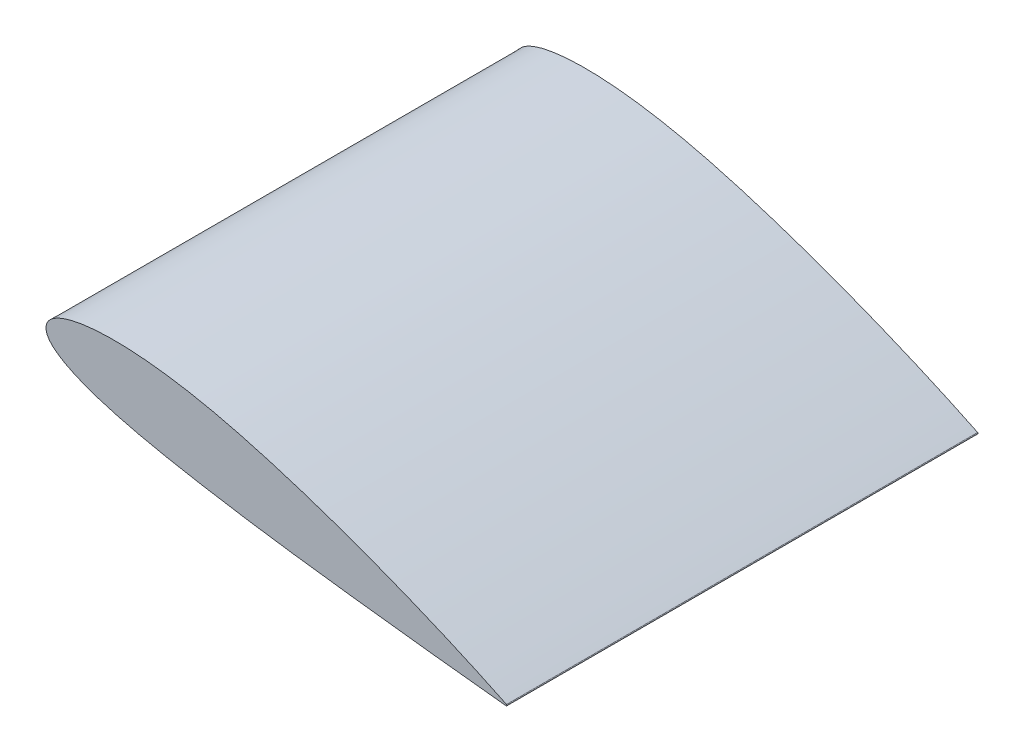
SolidWorks part; units mm, degrees
ref_plane "Front Plane"
ref_plane "Top Plane" through (0, 0, 0) normal (0, 1, 0) x (1, 0, 0)
ref_plane "Right Plane" through (0, 0, 0) normal (1, 0, 0) x (0, 0, -1)
curve "Curve1"
  spline degree 3 poles (25.4, 0.0399, 0) (25.378, 0.0455, 0) (25.2876, 0.0686, 0) (25.0833, 0.1169, 0) (24.7444, 0.1986, 0) (24.2743, 0.3079, 0) (23.6782, 0.4427, 0) (22.9624, 0.5992, 0) (22.1339, 0.7718, 0) (21.2017, 0.9572, 0) (20.1756, 1.1494, 0) (19.0665, 1.3442, 0) (17.8862, 1.536, 0) (16.6475, 1.7203, 0) (15.3641, 1.8922, 0) (14.0499, 2.0465, 0) (12.7195, 2.1793, 0) (11.3871, 2.2848, 0) (10.064, 2.3615, 0) (8.7644, 2.3973, 0) (7.5041, 2.3875, 0) (6.3019, 2.3314, 0) (5.1723, 2.2307, 0) (4.1285, 2.0871, 0) (3.1827, 1.9058, 0) (2.3457, 1.6908, 0) (1.6261, 1.4497, 0) (1.0314, 1.1874, 0) (0.5652, 0.911, 0) (0.2297, 0.6234, 0) (0.0247, 0.3197, 0) (-0.026, -0.0026, 0) (0.0875, -0.3078, 0) (0.3448, -0.5657, 0) (0.7235, -0.7848, 0) (1.2228, -0.973, 0) (1.8395, -1.1305, 0) (2.5685, -1.2568, 0) (3.4023, -1.3511, 0) (4.3324, -1.4141, 0) (5.3492, -1.447, 0) (6.4428, -1.4525, 0) (7.6021, -1.4335, 0) (8.8157, -1.3943, 0) (10.0756, -1.3404, 0) (11.3691, -1.2731, 0) (12.6822, -1.1887, 0) (13.997, -1.0934, 0) (15.2991, -0.9906, 0) (16.5743, -0.8837, 0) (17.8086, -0.7765, 0) (18.9885, -0.6699, 0) (20.1008, -0.5673, 0) (21.1332, -0.4696, 0) (22.074, -0.3787, 0) (22.9125, -0.2964, 0) (23.6391, -0.2232, 0) (24.2454, -0.161, 0) (24.7246, -0.1111, 0) (25.0709, -0.0749, 0) (25.2812, -0.0522, 0) (25.3756, -0.0424, 0) (25.4, -0.0399, 0) knots 0 0 0 0 0.001303 0.005353 0.012046 0.021311 0.033048 0.047117 0.063363 0.081612 0.101657 0.123274 0.146233 0.170278 0.195136 0.22054 0.246208 0.27186 0.297234 0.32226 0.346453 0.369544 0.391307 0.411513 0.42998 0.446543 0.46107 0.473486 0.48378 0.492064 0.498682 0.504377 0.51007 0.516665 0.524878 0.535025 0.54719 0.56136 0.577449 0.595324 0.614843 0.635824 0.658075 0.681379 0.705505 0.73044 0.755703 0.781015 0.806091 0.83066 0.85445 0.877193 0.898643 0.918556 0.936704 0.952884 0.966904 0.978612 0.987864 0.994552 0.998593 1 1 1 1
sketch "Sketch1" plane through (0, 0, 0) normal (0, 0, 1) x (1, 0, 0)
  line L0 (93.1686, -19.8036) -> (-31.0562, 6.6012) construction
  line L1 (-31.0562, 6.6012) -> (-25.7752, 31.4461) construction
  line L2 (91.0044, -19.8036) -> (-35.9956, -19.8036) construction
  arc A1 (93.0587, -19.5766) -> (92.9759, -19.9662) centre (92.9675, -19.7609) cw
  spline S1 degree 3 poles (93.0587, -19.5766) (92.957, -19.5263) (92.5395, -19.3198) (91.5919, -18.8714) (90.0209, -18.1208) (87.8382, -17.0988) (85.0665, -15.8213) (81.7323, -14.3133) (77.8644, -12.61) (73.5036, -10.7366) (68.6905, -8.7324) (63.475, -6.6295) (57.9086, -4.4671) (52.0496, -2.2803) (45.9587, -0.1083) (39.6995, 2.01) (33.3385, 4.0399) (26.9398, 5.9385) (20.5561, 7.6872) (14.2452, 9.2116) (8.0787, 10.4721) (2.1479, 11.4462) (-3.4745, 12.1274) (-8.7221, 12.5096) (-13.5305, 12.606) (-17.8423, 12.4246) (-21.6078, 11.9941) (-24.7852, 11.3308) (-27.3494, 10.4644) (-29.2867, 9.4077) (-30.6037, 8.1374) (-31.1859, 6.6154) (-30.9482, 5.0067) (-29.9591, 3.48) (-28.3368, 2.0165) (-26.0935, 0.5789) (-23.2442, -0.8309) (-19.8147, -2.205) (-15.8395, -3.531) (-11.3617, -4.8046) (-6.4288, -6.0212) (-1.0927, -7.1832) (4.5901, -8.2943) (10.5591, -9.3631) (16.7693, -10.4077) (23.1573, -11.422) (29.6593, -12.373) (36.1808, -13.2729) (42.648, -14.1225) (48.988, -14.9242) (55.1288, -15.6824) (61.0028, -16.3868) (66.5429, -17.0405) (71.6875, -17.6351) (76.3774, -18.1681) (80.5586, -18.6366) (84.1838, -19.0336) (87.2103, -19.3591) (89.6029, -19.6129) (91.3321, -19.7955) (92.3827, -19.9031) (92.8541, -19.9533) (92.9759, -19.9662) knots 0 0 0 0 0.001303 0.005353 0.012046 0.021311 0.033048 0.047117 0.063363 0.081612 0.101657 0.123274 0.146233 0.170278 0.195136 0.22054 0.246208 0.27186 0.297234 0.32226 0.346453 0.369544 0.391307 0.411513 0.42998 0.446543 0.46107 0.473486 0.48378 0.492064 0.498682 0.504377 0.51007 0.516665 0.524878 0.535025 0.54719 0.56136 0.577449 0.595324 0.614843 0.635824 0.658075 0.681379 0.705505 0.73044 0.755703 0.781015 0.806091 0.83066 0.85445 0.877193 0.898643 0.918556 0.936704 0.952884 0.966904 0.978612 0.987864 0.994552 0.998593 1 1 1 1
  point P3 (-31.0562, 6.6012)
  point P8 (0, 0)
  dimension "D1" = 127
  dimension "D2" = 31.75
  dimension "D3" = 12
extrude "Boss-Extrude1" add sketch "Sketch1" against normal blind 127 contours S1 A1
